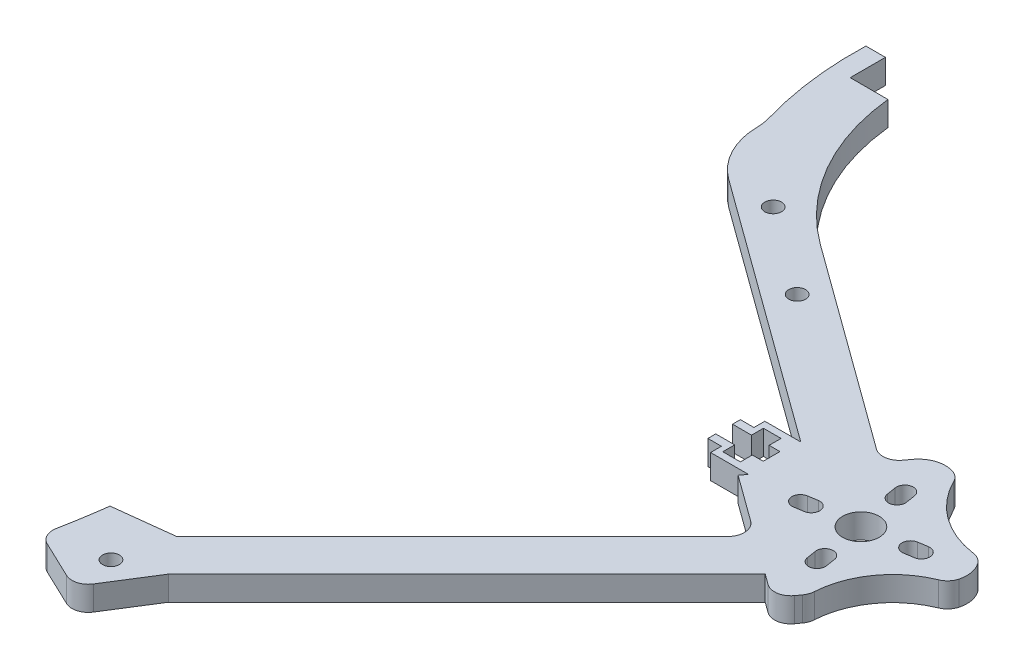
SolidWorks part; units mm, degrees
material "PPS"
ref_plane "前视基准面" through (0, 0, 0) normal (0, 0, 1) x (1, 0, 0)
ref_plane "上视基准面" through (0, 0, 0) normal (0, 1, 0) x (1, 0, 0)
ref_plane "右视基准面" through (0, 0, 0) normal (1, 0, 0) x (0, 0, -1)
sketch "草图3" plane through (0, 0, 0) normal (0, 1, 0) x (1, 0, 0)
  line L0 (0, 0) -> (35.4735, 0) construction
  line L1 (0, 0) -> (62.3757, -45.3186) construction
  line L2 (41.1319, -24.0128) -> (94.6944, -62.9282)
  line L3 (94.6944, -62.9282) -> (100.1314, -55.4448)
  line L4 (100.1314, -55.4448) -> (122.7839, -71.9028)
  line L5 (122.7839, -71.9028) -> (106.3259, -94.5552)
  line L6 (83.6734, -78.0972) -> (106.3259, -94.5552) construction
  line L9 (77.9994, -109.7251) -> (128.6275, -40.0415) construction
  line L11 (103.2286, -75) -> (90.242, -77.0569) construction
  line L13 (111.1302, -73.7485) -> (112.8586, -73.4748) construction
  line L14 (110.8877, -72.2176) -> (112.6161, -71.9438)
  line L15 (111.3726, -75.2794) -> (113.1011, -75.0057)
  line L16 (101.9772, -67.0985) -> (101.7034, -65.37) construction
  line L17 (103.5081, -66.856) -> (103.2343, -65.1276)
  line L18 (100.4463, -67.341) -> (100.1725, -65.6125)
  line L19 (95.3271, -76.2515) -> (93.5987, -76.5252) construction
  line L20 (95.5696, -77.7824) -> (93.8412, -78.0562)
  line L21 (95.0847, -74.7206) -> (93.3562, -74.9943)
  line L22 (104.4801, -82.9015) -> (104.7539, -84.63) construction
  line L23 (102.9492, -83.144) -> (103.223, -84.8724)
  line L24 (106.011, -82.659) -> (106.2848, -84.3875)
  line L25 (35.5479, -31.6984) -> (84.1364, -67)
  line L26 (84.1364, -67) -> (77.5, -67)
  line L27 (77.5, -67) -> (77.5, -69)
  line L28 (77.5, -69) -> (75, -69)
  line L29 (75, -69) -> (75, -70.45)
  line L30 (75, -70.45) -> (78.5, -70.45)
  line L31 (78.5, -70.45) -> (78.5, -68.25)
  line L32 (78.5, -68.25) -> (81.75, -68.25)
  line L33 (81.75, -68.25) -> (81.75, -70.45)
  line L34 (81.75, -70.45) -> (83.75, -70.45)
  line L35 (83.75, -70.45) -> (83.75, -73.55)
  line L36 (68.8077, -72) -> (90.242, -72) construction
  line L37 (81.75, -73.55) -> (83.75, -73.55)
  line L38 (81.75, -75.75) -> (81.75, -73.55)
  line L39 (78.5, -75.75) -> (81.75, -75.75)
  line L40 (78.5, -73.55) -> (78.5, -75.75)
  line L41 (75, -73.55) -> (78.5, -73.55)
  line L42 (75, -75) -> (75, -73.55)
  line L43 (77.5, -75) -> (75, -75)
  line L44 (77.5, -77) -> (77.5, -75)
  line L45 (84.1364, -77) -> (77.5, -77)
  line L47 (83.6734, -78.0972) -> (84.4706, -77)
  line L48 (84.4706, -77) -> (84.1364, -77)
  line L51 (41.6712, -139.6547) -> (94.9997, -86.3262)
  line L52 (94.9997, -86.3262) -> (83.6734, -78.0972)
  line L58 (46.9165, -146.4302) -> (101.962, -91.3847)
  line L61 (101.962, -91.3847) -> (106.3259, -94.5552)
  line L63 (30.9463, -152.7822) -> (40.1528, -157.1704)
  line L64 (46.9165, -146.4302) -> (40.1528, -157.1704)
  line L65 (41.6712, -139.6547) -> (30.6761, -140.942)
  circle A5 centre (103.2286, -75) radius 3.375
  arc A6 (110.8877, -72.2176) -> (111.3726, -75.2794) centre (111.1302, -73.7485) ccw
  arc A7 (113.1011, -75.0057) -> (112.6161, -71.9438) centre (112.8586, -73.4748) ccw
  arc A8 (103.5081, -66.856) -> (100.4463, -67.341) centre (101.9772, -67.0985) cw
  arc A9 (100.1725, -65.6125) -> (103.2343, -65.1276) centre (101.7034, -65.37) cw
  arc A10 (95.5696, -77.7824) -> (95.0847, -74.7206) centre (95.3271, -76.2515) ccw
  arc A11 (93.3562, -74.9943) -> (93.8412, -78.0562) centre (93.5987, -76.5252) ccw
  arc A12 (102.9492, -83.144) -> (106.011, -82.659) centre (104.4801, -82.9015) cw
  arc A13 (106.2848, -84.3875) -> (103.223, -84.8724) centre (104.7539, -84.63) cw
  arc A16 (41.1319, -24.0128) -> (35.5479, -31.6984) centre (38.3399, -27.8556) ccw
  circle A17 centre (103.2286, -75) radius 66.25 construction
  circle A18 centre (44.0442, -32) radius 1.55
  circle A19 centre (60.2246, -43.7557) radius 1.55
  circle A28 centre (39.335, -149.4323) radius 1.55
  arc A33 (30.6761, -140.942) -> (29.2902, -149.5124) centre (-122.812, -120.5195) cw
  arc A35 (29.2902, -149.5124) -> (30.9463, -152.7822) centre (32.2371, -150.0741) ccw
  point P11 (114.5549, -83.229)
  point P20 (111.9944, -73.6116)
  point P27 (101.8403, -66.2343)
  point P35 (94.4629, -76.3884)
  point P42 (104.617, -83.7657)
  point P54 (94.9997, -86.3262)
  point P67 (83.75, -72)
  dimension "D2" = 45
  dimension "D3" = 6.75
  dimension "D4" = 1.55
  dimension "D7" = 14
  dimension "D11" = 132.5
  dimension "D12" = 3.1
  dimension "D26" = 8.5
  dimension "D27" = 3.1
  dimension "D1" = 36
  dimension "D5" = 1.75
  dimension "D6" = 8
  dimension "D8" = 14
  dimension "D9" = 4.75
  dimension "D10" = 75
  dimension "D13" = 32
  dimension "D14" = 20
  dimension "D15" = 7.5
  dimension "D16" = 10
  dimension "D17" = 3.1
  dimension "D18" = 3.5
  dimension "D19" = 3.25
  dimension "D20" = 2
  dimension "D21" = 2.5
  dimension "D22" = 72
  dimension "D23" = 75
  dimension "D24" = 1.45
  dimension "D25" = 45
extrude "凸台-拉伸1" add sketch "草图3" along normal blind 4.5
fillet "圆角-美观1" radius 5 2 edges at (100.1314, 2.25, 55.4448) (122.7839, 2.25, 71.9028)
sketch "草图4" plane through (0, 4.5, 0) normal (0, 1, 0) x (1, 0, 0)
  line L0 (104.1765, -58.3837) -> (118.7388, -68.9638)
  line L1 (119.8449, -75.9478) -> (109.2648, -90.5101)
  line L3 (103.2286, -75) -> (124.6569, -90.5685) construction
  line L4 (103.2286, -75) -> (89.033, -94.5387) construction
  line L5 (87.7185, -81.0362) -> (102.2808, -91.6163)
  line L7 (41.1319, -24.0128) -> (94.6944, -62.9282) construction
  arc A2 (102.2808, -91.6163) -> (87.7185, -81.0362) centre (86.1651, -98.4859) ccw
  arc A8 (118.7388, -68.9638) -> (104.1765, -58.3837) centre (120.2922, -51.5141) cw
  arc A9 (119.8449, -75.9478) -> (109.2648, -90.5101) centre (124.6569, -90.5685) ccw
extrude "圆弧-美观2" cut sketch "草图4" against normal up to next contours A8 L0 | L1 A9
fillet "圆角-美观3" radius 3 8 edges at (104.1765, 2.25, 58.3837) (118.7388, 2.25, 68.9638) (119.8449, 2.25, 75.9478) (94.6944, 2.25, 62.9282) (109.2648, 2.25, 90.5101) (94.9997, 2.25, 86.3262) (106.3259, 2.25, 94.5552) (40.1528, 2.25, 157.1704)
sketch "草图5" plane through (0, 0, 0) normal (0, 1, 0) x (1, 0, 0)
  line L0 (0, 0) -> (132.1913, 0) construction
  line L1 (0, 0) -> (0, 63.0505) construction
  line L2 (41.1319, -24.0128) -> (54.395, -33.649)
  line L3 (30.5, 2.25) -> (26.9026, 2.25)
  line L4 (30.5, 2.25) -> (30.5, -3.25)
  line L5 (30.5, -3.25) -> (30.5, -4.25)
  line L6 (30.5, -4.25) -> (37.4677, -4.25)
  line L7 (41.1319, -24.0128) -> (92.2673, -61.1648) construction
  line L8 (37.3772, -3.25) -> (30.5, -3.25) construction
  line L9 (30.5, -3.25) -> (30.5, 3.25) construction
  line L10 (30.5, 3.25) -> (26.9448, 3.25) construction
  line L11 (41.1319, -24.0128) -> (35.5479, -31.6984)
  line L13 (34.4971, -25.0636) -> (29.8517, -19.5014) construction
  arc A0 (34.4971, -25.0636) -> (41.1319, -24.0128) centre (38.3399, -27.8556) cw construction
  arc A1 (34.4971, -25.0636) -> (35.5479, -31.6984) centre (38.3399, -27.8556) ccw construction
  arc A2 (29.8211, -20.7007) -> (35.5479, -31.6984) centre (43.7171, -20.4546) ccw
  arc A3 (29.8211, -20.7007) -> (29.4289, -18.099) centre (19.8227, -20.8778) ccw
  arc A6 (26.9026, 2.25) -> (29.4289, -18.099) centre (91.9966, 0) ccw
  arc A7 (29.8202, 19.4008) -> (29.8202, -19.4008) centre (91.9966, 0) ccw construction
  arc A8 (54.395, -33.649) -> (37.3772, -3.25) centre (78.8424, 0) cw construction
  arc A9 (29.4289, -18.099) -> (26.9448, 3.25) centre (91.9966, 0) cw construction
  arc A12 (41.1319, -24.0128) -> (35.5479, -31.6984) centre (38.3399, -27.8556) ccw construction
  arc A14 (54.395, 33.649) -> (54.395, -33.649) centre (78.8424, 0) ccw construction
  arc A15 (37.4677, -4.25) -> (42.5499, -20.3171) centre (78.8424, 0) ccw
  arc A16 (54.395, -33.649) -> (42.5499, -20.3171) centre (78.8424, 0) cw
  dimension "D1" = 3.25
  dimension "D5" = 1
  dimension "D2" = 3.25
  dimension "D3" = 30.5
  dimension "D4" = 1
extrude "机臂配合防旋转" add sketch "草图5" along normal up to surface (4.5 mm away) up to face at (39.335, 4.5, 150.9823)
